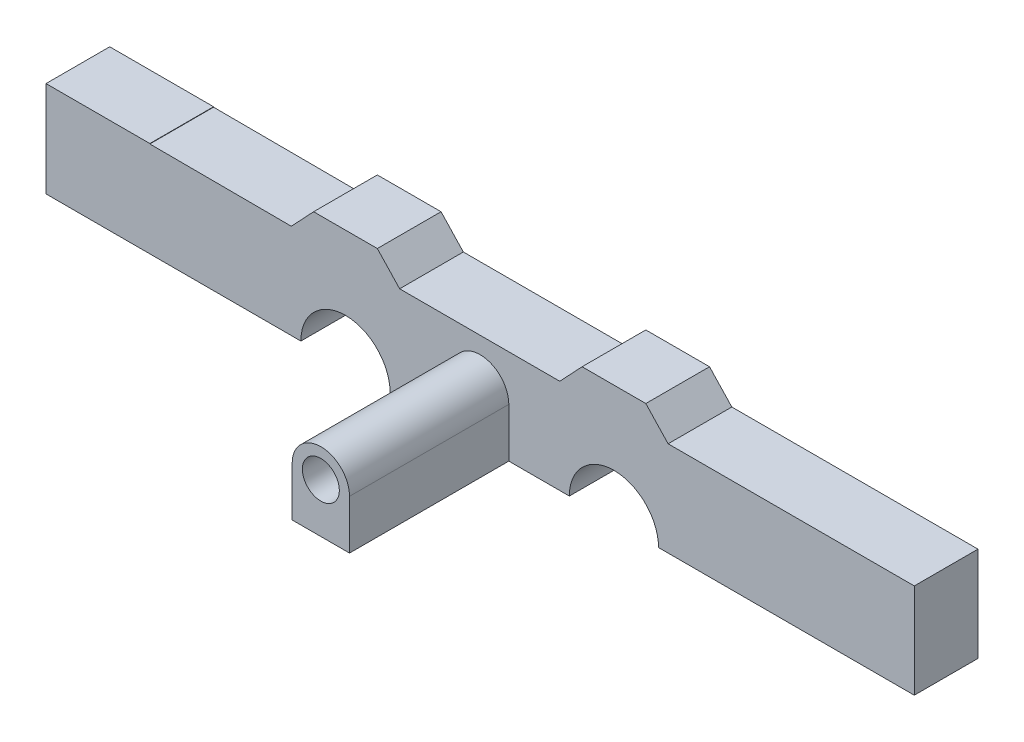
SolidWorks part; units mm, degrees
ref_plane "Front" through (0, 0, 0) normal (0, 0, 1) x (1, 0, 0)
ref_plane "Top" through (0, 0, 0) normal (0, 1, 0) x (1, 0, 0)
ref_plane "Right" through (0, 0, 0) normal (1, 0, 0) x (0, 0, -1)
sketch "Sketch1" plane through (0, 0, 0) normal (0, 0, 1) x (1, 0, 0)
  line L0 (0, 0) -> (0, 15)
  line L1 (81.5002, 12.8569) -> (54.6343, 12.8569)
  line L2 (0, 0) -> (40, 0)
  line L3 (54, 0) -> (82.1345, 0)
  line L4 (68.0673, 0) -> (68.0673, 41.3937) construction
  line L5 (80.6352, 14.8569) -> (55.4993, 14.8569)
  line L6 (0, 15) -> (38.5007, 14.8569)
  line L7 (42, 18.5807) -> (38.5007, 14.8569)
  line L8 (84.1345, 18.5807) -> (80.6352, 14.8569)
  line L9 (89.1345, -5.0592) -> (89.1345, 29.2336) construction
  line L10 (42, 18.5807) -> (47, 18.5807)
  line L11 (52, 18.5807) -> (47, 18.5807)
  line L12 (52, 18.5807) -> (55.4993, 14.8569)
  line L13 (84.1345, 18.5807) -> (89.1345, 18.5807)
  line L14 (94.1345, 18.5807) -> (89.1345, 18.5807)
  line L15 (94.1345, 18.5807) -> (97.6338, 14.8569)
  line L16 (96.1345, 0) -> (136.1345, 0)
  line L17 (136.1345, 0) -> (136.1345, 14.8569)
  line L18 (136.1345, 14.8569) -> (97.6338, 14.8569)
  line L19 (2, 12.8569) -> (39.3657, 12.8569)
  line L20 (42.8651, 16.5807) -> (39.3657, 12.8569)
  line L21 (42.8651, 16.5807) -> (47, 16.5807)
  line L22 (51.1349, 16.5807) -> (47, 16.5807)
  line L23 (51.1349, 16.5807) -> (54.6343, 12.8569)
  line L24 (84.9996, 16.5807) -> (81.5002, 12.8569)
  line L25 (84.9996, 16.5807) -> (89.1345, 16.5807)
  line L26 (93.2694, 16.5807) -> (89.1345, 16.5807)
  line L27 (93.2694, 16.5807) -> (96.7688, 12.8569)
  line L28 (134.1345, 12.8569) -> (96.7688, 12.8569)
  line L29 (134.1345, 2) -> (134.1345, 12.8569)
  line L30 (97.9095, 2) -> (134.1345, 2)
  line L31 (55.775, 2) -> (80.3595, 2)
  line L32 (2, 2) -> (38.225, 2)
  line L33 (2, 2) -> (2, 12.8569)
  line L34 (35.9885, 12.5106) -> (36.2663, 10.0223) construction
  line L35 (34.186, 10.6305) -> (34.7627, 5.465) construction
  line L36 (36.2663, 10.0223) -> (40.7574, 14.8569) construction
  line L37 (34.7627, 5.465) -> (41.6293, 12.8569) construction
  line L38 (62.195, 12.8569) -> (41.6293, 12.8569) construction
  line L39 (62.195, 14.8569) -> (40.7574, 14.8569) construction
  line L40 (81.5002, 12.8569) -> (62.195, 12.8569) construction
  line L41 (80.6352, 14.8569) -> (62.195, 14.8569) construction
  line L42 (2, 12.8569) -> (34.186, 10.6305) construction
  line L43 (0, 15) -> (35.9885, 12.5106) construction
  arc A0 (40, 0) -> (54, 0) centre (47, 0) cw
  arc A1 (82.1345, 0) -> (96.1345, 0) centre (89.1345, 0) cw
  arc A2 (80.3595, 2) -> (97.9095, 2) centre (89.1345, 0) cw
  arc A3 (38.225, 2) -> (55.775, 2) centre (47, 0) cw
  point P22 (89.1345, 13.4472)
  point P25 (89.1345, 13.8412)
  point P46 (68.0673, 14.8569)
  point P55 (68.0673, 12.8569)
  dimension "D3" = 7
  dimension "D5" = 7
  dimension "D2" = 2
  dimension "D13" = 2
extrude "Boss-Extrude1" add sketch "Sketch1" along normal blind 10
sketch "Sketch2" plane through (0, 0, 10) normal (0, 0, 1) x (1, 0, 0)
  line L14 (0, 0) -> (40, 0)
  line L15 (54, 0) -> (82.1345, 0)
  line L16 (96.1345, 0) -> (136.1345, 0)
  line L17 (136.1345, 0) -> (136.1345, 14.8569)
  line L18 (136.1345, 0) -> (136.1345, 14.8569)
  line L19 (136.1345, 14.8569) -> (97.6338, 14.8569)
  line L20 (136.1345, 14.8569) -> (97.6338, 14.8569)
  line L21 (97.6338, 14.8569) -> (94.1345, 18.5807)
  line L22 (97.6338, 14.8569) -> (94.1345, 18.5807)
  line L23 (80.6352, 14.8569) -> (55.4993, 14.8569)
  line L24 (80.6352, 14.8569) -> (55.4993, 14.8569)
  line L25 (55.4993, 14.8569) -> (52, 18.5807)
  line L26 (55.4993, 14.8569) -> (52, 18.5807)
  line L27 (0, 15) -> (0, 0)
  line L28 (0, 0) -> (40, 0)
  line L29 (54, 0) -> (82.1345, 0)
  line L30 (96.1345, 0) -> (136.1345, 0)
  line L31 (94.1345, 18.5807) -> (84.1345, 18.5807)
  line L32 (94.1345, 18.5807) -> (84.1345, 18.5807)
  line L33 (84.1345, 18.5807) -> (80.6352, 14.8569)
  line L34 (84.1345, 18.5807) -> (80.6352, 14.8569)
  line L35 (52, 18.5807) -> (42, 18.5807)
  line L36 (52, 18.5807) -> (42, 18.5807)
  line L37 (42, 18.5807) -> (38.5007, 14.8569)
  line L38 (42, 18.5807) -> (38.5007, 14.8569)
  line L39 (38.5007, 14.8569) -> (0, 15)
  line L40 (38.5007, 14.8569) -> (0, 15)
  line L41 (0, 15) -> (0, 0)
  arc A2 (54, 0) -> (40, 0) centre (47, 0) ccw
  arc A3 (96.1345, 0) -> (82.1345, 0) centre (89.1345, 0) ccw
  arc A4 (54, 0) -> (40, 0) centre (47, 0) ccw
  arc A5 (96.1345, 0) -> (82.1345, 0) centre (89.1345, 0) ccw
  dimension "D1" = 0
extrude "Boss-Extrude2" add sketch "Sketch2" against normal blind 2
sketch "Sketch3" plane through (0, 0, 0) normal (0, 0, -1) x (-1, 0, 0)
  line L14 (-40, 0) -> (0, 0)
  line L15 (0, 0) -> (0, 15)
  line L16 (0, 15) -> (-38.5007, 14.8569)
  line L17 (0, 15) -> (-38.5007, 14.8569)
  line L18 (-38.5007, 14.8569) -> (-42, 18.5807)
  line L19 (-38.5007, 14.8569) -> (-42, 18.5807)
  line L20 (-42, 18.5807) -> (-52, 18.5807)
  line L21 (-42, 18.5807) -> (-52, 18.5807)
  line L22 (-80.6352, 14.8569) -> (-84.1345, 18.5807)
  line L23 (-80.6352, 14.8569) -> (-84.1345, 18.5807)
  line L24 (-84.1345, 18.5807) -> (-94.1345, 18.5807)
  line L25 (-84.1345, 18.5807) -> (-94.1345, 18.5807)
  line L26 (-136.1345, 0) -> (-96.1345, 0)
  line L27 (-82.1345, 0) -> (-54, 0)
  line L28 (-40, 0) -> (0, 0)
  line L29 (0, 0) -> (0, 15)
  line L30 (-52, 18.5807) -> (-55.4993, 14.8569)
  line L31 (-52, 18.5807) -> (-55.4993, 14.8569)
  line L32 (-55.4993, 14.8569) -> (-80.6352, 14.8569)
  line L33 (-55.4993, 14.8569) -> (-80.6352, 14.8569)
  line L34 (-94.1345, 18.5807) -> (-97.6338, 14.8569)
  line L35 (-94.1345, 18.5807) -> (-97.6338, 14.8569)
  line L36 (-97.6338, 14.8569) -> (-136.1345, 14.8569)
  line L37 (-97.6338, 14.8569) -> (-136.1345, 14.8569)
  line L38 (-136.1345, 14.8569) -> (-136.1345, 0)
  line L39 (-136.1345, 14.8569) -> (-136.1345, 0)
  line L40 (-136.1345, 0) -> (-96.1345, 0)
  line L41 (-82.1345, 0) -> (-54, 0)
  arc A2 (-82.1345, 0) -> (-96.1345, 0) centre (-89.1345, 0) ccw
  arc A3 (-40, 0) -> (-54, 0) centre (-47, 0) ccw
  arc A4 (-82.1345, 0) -> (-96.1345, 0) centre (-89.1345, 0) ccw
  arc A5 (-40, 0) -> (-54, 0) centre (-47, 0) ccw
  dimension "D1" = 0
extrude "Boss-Extrude3" add sketch "Sketch3" against normal blind 2
sketch "Sketch6" plane through (0, 0, 10) normal (0, 0, 1) x (1, 0, 0)
  line L0 (136.1345, 0) -> (136.1345, 14.8569) construction
  circle A0 centre (68.1345, 7.7173) radius 4.5
  circle A1 centre (68.1345, 7.7173) radius 2.9
  dimension "D1" = 5.8
  dimension "D2" = 9
  dimension "D3" = 68
extrude "Boss-Extrude4" add sketch "Sketch6" along normal blind 25
sketch "Sketch7" plane through (0, 0, 10) normal (0, 0, 1) x (1, 0, 0)
  circle A0 centre (68.1345, 7.7173) radius 2.9
extrude "Cut-Extrude1" cut sketch "Sketch7" against normal blind 8
sketch "Sketch9" plane through (0, 0, 10) normal (0, 0, 1) x (1, 0, 0)
  line L0 (136.1345, 14.8569) -> (97.6338, 14.8569) construction
  line L1 (68.1345, 7.7173) -> (68.1345, 46.1216) construction
  line L2 (136.1345, 0) -> (136.1345, 14.8569) construction
  line L3 (68.1345, 46.1216) -> (68.1345, -9.2458) construction
  circle A0 centre (126.1345, 7.3569) radius 2.5
  circle A1 centre (103, 7.5) radius 2.5
  circle A2 centre (80.1345, 7.5) radius 2.5
  circle A3 centre (68.1345, 7.7173) radius 2.9 construction
  circle A4 centre (10.1345, 7.3569) radius 2.5
  circle A5 centre (33.269, 7.5) radius 2.5
  circle A6 centre (56.1345, 7.5) radius 2.5
  dimension "D1" = 5
  dimension "D2" = 7.5
  dimension "D4" = 5
  dimension "D5" = 5
  dimension "D6" = 12
  dimension "D3" = 10
extrude "Boss-Extrude5" add sketch "Sketch9" against normal up to surface (10 mm away) up to face at (68.0673, 11.1004, 0)
sketch "Sketch10" plane through (0, 0, 35) normal (0, 0, 1) x (1, 0, 0)
  line L0 (63.6345, 7.7173) -> (63.6345, 0)
  line L1 (54, 0) -> (82.1345, 0) construction
  line L2 (63.6345, 0) -> (72.6345, 0)
  line L3 (72.6345, 0) -> (72.6345, 7.7173)
  arc A0 (63.6345, 7.7173) -> (72.6345, 7.7173) centre (68.1345, 7.7173) ccw
  circle A1 centre (68.1345, 7.7173) radius 4.5 construction
extrude "Boss-Extrude6" add sketch "Sketch10" against normal up to surface (25 mm away) up to face at (68.0673, 11.1004, 10)
sketch "Sketch13" plane through (0, 0, 0) normal (0, -1, 0) x (1, 0, 0)
  line L2 (0, 10) -> (0, 0)
  line L3 (16.2978, 10) -> (0, 10)
  line L4 (0, 0) -> (16.2978, 0)
  line L5 (16.2978, 10) -> (16.2978, 0)
  line L6 (0, 0) -> (40, 0) construction
  line L7 (68.1345, 35) -> (68.1345, -4.6682) construction
  line L8 (63.6345, 35) -> (72.6345, 35) construction
  line L9 (136.269, 0) -> (119.9712, 0)
  line L10 (119.9712, 10) -> (119.9712, 0)
  line L11 (119.9712, 10) -> (136.269, 10)
  line L12 (136.269, 10) -> (136.269, 0)
  dimension "D1" = 16.2978
extrude "Boss-Extrude7" add sketch "Sketch13" against normal blind 15
sketch "Sketch14" plane through (0, 0, 0) normal (0, -1, 0) x (1, 0, 0)
  line L0 (12, 7.1) -> (12, 2.2656) construction
  line L1 (9, 7.1) -> (15, 7.1)
  line L2 (9, 7.1) -> (9, 2.9)
  line L3 (9, 2.9) -> (15, 2.9)
  line L4 (15, 7.1) -> (15, 2.9)
  line L5 (9, 5) -> (15, 5) construction
  line L6 (40, 5) -> (54, 5) construction
  line L7 (40, 10) -> (40, 0) construction
  line L8 (54, 10) -> (54, 0) construction
  line L9 (47, 5) -> (47, 15.522) construction
  line L15 (0, 10) -> (40, 10) construction
  line L16 (68.1345, 35) -> (68.1345, -2.542) construction
  line L17 (63.6345, 35) -> (72.6345, 35) construction
  line L18 (127.269, 2.9) -> (121.269, 2.9)
  line L19 (121.269, 7.1) -> (121.269, 2.9)
  line L20 (127.269, 7.1) -> (121.269, 7.1)
  line L21 (127.269, 7.1) -> (127.269, 2.9)
  dimension "D1" = 4.2
  dimension "D2" = 6
  dimension "D3" = 38
  dimension "D4" = 5
extrude "Cut-Extrude4" cut sketch "Sketch14" against normal blind 8
sketch "Sketch17" plane through (119.9712, 0, 0) normal (-1, 0, 0) x (0, 0, 1)
  line L1 (0, 14.8569) -> (10, 14.8569)
  line L2 (0, 14.8569) -> (0, 15)
  line L3 (0, 15) -> (10, 15)
  line L4 (10, 14.8569) -> (10, 15)
extrude "Cut-Extrude5" cut sketch "Sketch17" against normal up to surface (16.2978 mm away) up to face at (136.269, 7.5, 5)
sketch "Sketch18" plane through (0, 0, 0) normal (0, 0, -1) x (-1, 0, 0)
  line L0 (-96.1345, 0) -> (-96.1345, 25.5796) construction
  line L1 (-136.269, 14.8569) -> (-96.1345, 0) construction
  line L2 (-68.0673, 14.8569) -> (-68.0673, -9.5541) construction
  line L3 (-80.6352, 14.8569) -> (-55.4993, 14.8569) construction
  circle A0 centre (-116.2018, 7.4284) radius 3
  circle A1 centre (-19.9327, 7.4284) radius 3
  dimension "D1" = 6
extrude "Cut-Extrude6" cut sketch "Sketch18" against normal blind 3
